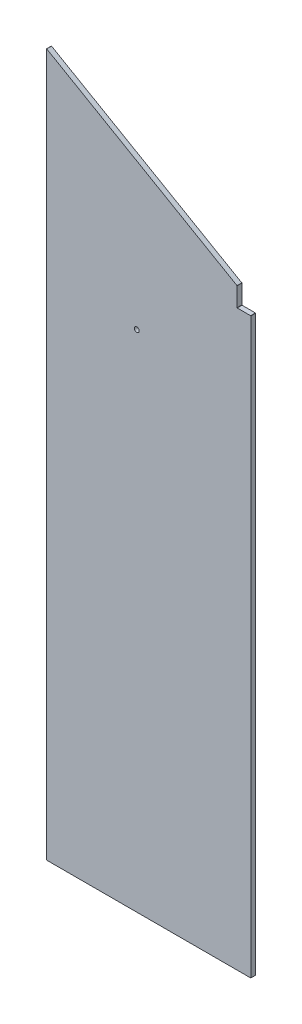
SolidWorks part; units mm, degrees
material "PE High Density"
ref_plane "Front Plane" through (0, 0, 0) normal (0, 0, 1) x (1, 0, 0)
ref_plane "Top Plane" through (0, 0, 0) normal (0, 1, 0) x (1, 0, 0)
ref_plane "Right Plane" through (0, 0, 0) normal (1, 0, 0) x (0, 0, -1)
sketch "Sketch1" plane through (0, 0, 0) normal (0, 0, 1) x (1, 0, 0)
  line L7 (270.002, 0) -> (270.002, 757.8937)
  line L8 (0, 928.7609) -> (251.9565, 783.2937)
  line L9 (0, 0) -> (0, 928.7609)
  line L10 (270.002, 0) -> (0, 0)
  line L14 (251.9565, 783.2937) -> (251.9565, 757.8937)
  line L16 (251.9565, 757.8937) -> (270.002, 757.8937)
  point P1 (272.415, 0)
  point P3 (0, 928.37)
  point P5 (272.415, 787.8064)
  point P9 (269.5829, 2.8321)
  point P10 (269.5829, 786.0808)
  dimension "D1" = 270.002
  dimension "D2" = 25.4
  dimension "D3" = 928.7609
  dimension "D4" = 18.0455
  dimension "D5" = 60
extrude "Boss-Extrude1" add sketch "Sketch1" along normal blind 6.35
fillet "Fillet2" radius 0.254 5 edges at (0, 928.7609, 3.175) (270.002, 757.8937, 3.175) (0, 0, 3.175) (251.9565, 757.8937, 3.175) (251.9565, 783.2937, 3.175)
sketch "Sketch2" plane through (0, 0, 6.35) normal (0, 0, 1) x (1, 0, 0)
  line L0 (0, 928.321) -> (0, 0.254) construction
  line L1 (0.254, 0) -> (270.002, 0) construction
  circle A0 centre (119.38, 666.75) radius 3.175
  dimension "D1" = 6.35
  dimension "D2" = 119.38
  dimension "D3" = 666.75
extrude "Cut-Extrude1" cut sketch "Sketch2" against normal through all
